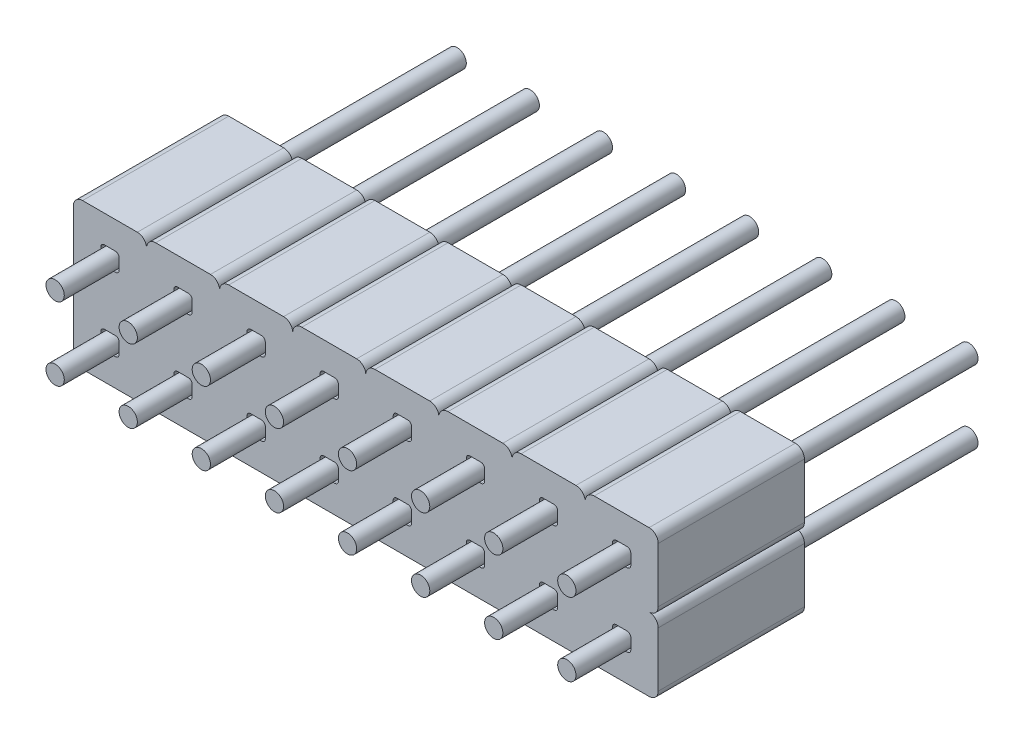
SolidWorks part; units mm, degrees
ref_plane "前视基准面" through (0, 0, 0) normal (0, 0, 1) x (1, 0, 0)
ref_plane "上视基准面" through (0, 0, 0) normal (0, 1, 0) x (1, 0, 0)
ref_plane "右视基准面" through (0, 0, 0) normal (1, 0, 0) x (0, 0, -1)
sketch "草图1" plane through (0, 0, 0) normal (0, 0, 1) x (1, 0, 0)
  line L0 (1, 0) -> (1, -2) construction
  line L1 (0.25, 0) -> (1.75, 0)
  line L2 (0, -0.25) -> (0, -1.75)
  line L3 (0.25, -2) -> (1.75, -2)
  line L4 (2, -0.25) -> (2, -1.75)
  line L5 (0, -1) -> (2, -1) construction
  line L7 (0.85, -0.75) -> (1.15, -0.75)
  line L8 (0.75, -0.85) -> (0.75, -1.15)
  line L9 (0.85, -1.25) -> (1.15, -1.25)
  line L10 (1.25, -0.85) -> (1.25, -1.15)
  arc A0 (2, -1.75) -> (1.75, -2) centre (1.75, -1.75) cw
  arc A1 (0.25, -2) -> (0, -1.75) centre (0.25, -1.75) cw
  arc A2 (0.25, 0) -> (0, -0.25) centre (0.25, -0.25) ccw
  arc A3 (2, -0.25) -> (1.75, 0) centre (1.75, -0.25) ccw
  circle A4 centre (1, -1) radius 0.25 construction
  arc A5 (0.75, -1.15) -> (0.85, -1.25) centre (0.85, -1.15) ccw
  arc A6 (1.15, -1.25) -> (1.25, -1.15) centre (1.15, -1.15) ccw
  arc A7 (1.25, -0.85) -> (1.15, -0.75) centre (1.15, -0.85) ccw
  arc A8 (0.85, -0.75) -> (0.75, -0.85) centre (0.85, -0.85) ccw
  point P11 (0, 0)
  dimension "D3" = 0.25
  dimension "D4" = 0.5
  dimension "D5" = 0.1
  dimension "D1" = 2
  dimension "D2" = 2
extrude "凸台-拉伸1" add sketch "草图1" along normal blind 4
pattern_linear "阵列(线性)2" count 8 spacing 2 along (1, 0, 0) count 2 spacing 2 along (0, -1, 0) of "凸台-拉伸1"
sketch "草图3" plane through (0, 0, 0) normal (0, 0, -1) x (-1, 0, 0)
  line L0 (-1, 0) -> (-1, -4) construction
  line L1 (-1.75, 0) -> (-0.25, 0) construction
  line L2 (-0.25, -4) -> (-1.75, -4) construction
  line L3 (0, -1) -> (-2.4529, -1) construction
  line L4 (0, -0.25) -> (0, -1.75) construction
  line L5 (-0.25, -2) -> (-1.75, -2) construction
  line L9 (-0.75, -0.85) -> (-0.75, -1.15) construction
  line L10 (-0.85, -1.25) -> (-1.15, -1.25) construction
  line L11 (-1.25, -0.85) -> (-1.25, -1.15) construction
  line L12 (-0.85, -0.75) -> (-1.15, -0.75) construction
  circle A0 centre (-1, -1) radius 0.25
  arc A4 (-1.25, -1.15) -> (-1.15, -1.25) centre (-1.15, -1.15) ccw construction
  arc A5 (-0.75, -1.15) -> (-0.85, -1.25) centre (-0.85, -1.15) cw construction
  arc A6 (-0.85, -0.75) -> (-0.75, -0.85) centre (-0.85, -0.85) cw construction
  arc A7 (-1.15, -0.75) -> (-1.25, -0.85) centre (-1.15, -0.85) ccw construction
  point P26 (-1, -1.25)
  point P28 (-0.75, -1)
  point P29 (-1.25, -1)
  point P31 (-1.25, -1.25)
  point P34 (-0.75, -1.25)
  point P37 (-0.75, -0.75)
  point P40 (-1.25, -0.75)
  dimension "D4" = 0.1
  dimension "D2" = 0.25
  dimension "D3" = 0.25
ref_plane "基准面1" through (1, 0, 0) normal (-1, 0, 0) x (0, 0, 1)
ref_plane "基准面2" through (0, -2, 0) normal (0, -1, 0) x (1, 0, 0)
extrude "凸台-拉伸2" add sketch "草图3" along normal mid plane 11 separate body
pattern_linear "阵列(线性)3" count 8 spacing 2 along (1, 0, 0) count 2 spacing 2 along (0, -1, 0) of "凸台-拉伸2"
